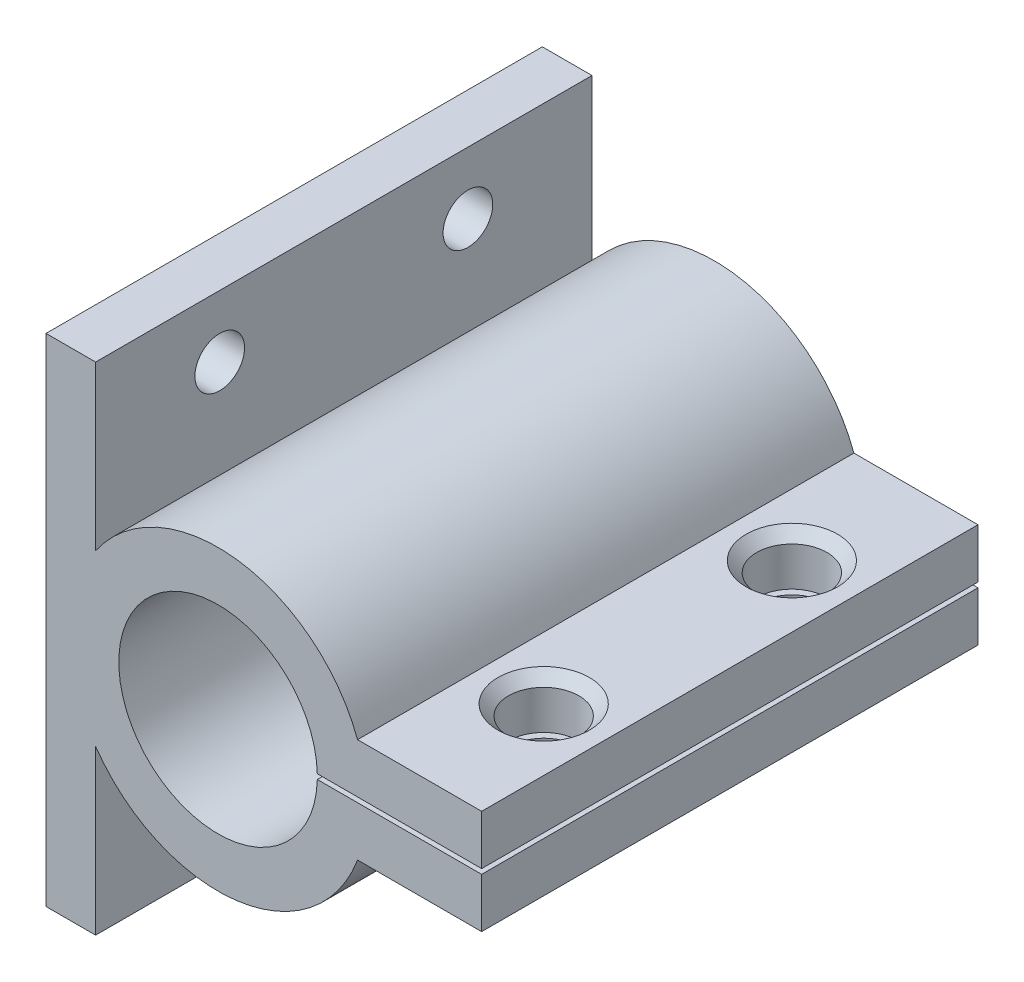
SolidWorks part; units mm, degrees
ref_plane "前视基准面" through (0, 0, 0) normal (0, 0, 1) x (1, 0, 0)
ref_plane "上视基准面" through (0, 0, 0) normal (0, 1, 0) x (1, 0, 0)
ref_plane "右视基准面" through (0, 0, 0) normal (1, 0, 0) x (0, 0, -1)
sketch "草图1" plane through (0, 0, 0) normal (0, 0, 1) x (1, 0, 0)
  line L0 (0, 2.819) -> (-22.3413, 2.819) construction
  line L1 (-34.3169, -27.181) -> (-34.3169, 32.819)
  line L2 (-34.3169, 32.819) -> (-28.3169, 32.819)
  line L3 (-28.3169, 32.819) -> (-28.3169, 13.0626)
  line L4 (3.3455, 9.119) -> (18.3455, 9.119)
  line L5 (18.3455, 9.119) -> (18.3455, 3.119)
  line L6 (18.3455, 3.119) -> (-1.5197, 3.119)
  line L7 (18.3455, 2.519) -> (-1.5197, 2.519)
  line L8 (18.3455, -3.481) -> (18.3455, 2.519)
  line L9 (3.3455, -3.481) -> (18.3455, -3.481)
  line L10 (-28.3169, -27.181) -> (-28.3169, -7.4247)
  line L11 (-34.3169, -27.181) -> (-28.3169, -27.181)
  arc A0 (-28.3169, 13.0626) -> (3.3455, 9.119) centre (-13.516, 2.819) cw
  arc A1 (-1.5197, 3.119) -> (-1.5197, 2.519) centre (-13.516, 2.819) ccw
  arc A2 (-28.3169, -7.4247) -> (3.3455, -3.481) centre (-13.516, 2.819) ccw
  point P13 (0, 0)
  point P14 (0, 0)
  point P21 (-34.3169, 2.819)
  dimension "D1" = 30
  dimension "D6" = 24
  dimension "D5" = 0.3
  dimension "D7" = 6
  dimension "D2" = 6
  dimension "D3" = 15
  dimension "D4" = 6
extrude "凸台-拉伸1" add sketch "草图1" along normal blind 60
sketch "草图2" plane through (-28.3169, 0, 0) normal (1, 0, 0) x (0, 0, -1)
  line L0 (-60, 32.819) -> (0, 32.819) construction
  line L1 (-60, 13.0626) -> (-60, 32.819) construction
  line L2 (0, 13.0626) -> (0, 32.819) construction
  circle A0 centre (-45, 25.319) radius 3
  circle A1 centre (-15, 25.319) radius 3
  point P6 (0, 0)
  point P8 (-60, 24.8462)
  point P14 (-13.3036, 32.819)
  dimension "D1" = 7.5
  dimension "D3" = 6
  dimension "D4" = 6
  dimension "D2" = 15
  dimension "D5" = 15
  dimension "D6" = 7.5
extrude "切除-拉伸1" cut sketch "草图2" against normal through all
ref_plane "基准面1" through (0, 2.819, 0) normal (0, 1, 0) x (1, 0, 0)
mirror "镜向3" about plane through (0, 2.819, 0) normal (0, 1, 0) of "切除-拉伸1"
ref_plane "基准面2" through (0, 9.119, 0) normal (0, 1, 0) x (1, 0, 0)
hole_wizard "M10 螺纹孔1" positions "3D草图1" profile "草图6" tap size "M10" standard "ISO"
sketch3d "3D草图1"
  line L0 (18.3455, 9.119, 0) -> (3.3455, 9.119, 0) construction
  line L1 (18.3455, 9.119, 60) -> (18.3455, 9.119, 0) construction
  line L3 (18.3455, 9.119, 60) -> (3.3455, 9.119, 60) construction
  point P0 (10.8455, 9.119, 15)
  point P2 (10.8455, 9.119, 45)
  dimension "D1" = 15
  dimension "D2" = 7.5
  dimension "D3" = 7.5
  dimension "D4" = 15
sketch "草图6" plane through (10.8455, 9.119, 15) normal (1, 0, 0) x (0, 0, 1)
  line L0 (0, 0) -> (0, 30.0537)
  line L1 (0, 30.0537) -> (4.25, 27.5)
  line L2 (4.25, 27.5) -> (4.25, 1.275)
  line L3 (4.25, 1.275) -> (5.525, 0)
  line L5 (5.525, 0) -> (0, 0)
  line L6 (-4.25, 1.275) -> (-5.525, 0) construction
  line L10 (0, 30.0537) -> (-4.25, 27.5) construction
  line L11 (0, -6.35) -> (0, 107.95) construction
  dimension "螺纹孔钻头直径" = 8.5
  dimension "螺纹孔钻头深度" = 27.5
  dimension "近端锥形沉头孔直径" = 11.05
  dimension "近端锥形沉头孔角度" = 90
  dimension "导头角度" = 118
cosmetic thread "孔螺蚊线1" parameters "D1"=12.6, "D2"=10
cosmetic thread "孔螺蚊线2" parameters "D1"=12.6, "D2"=10
